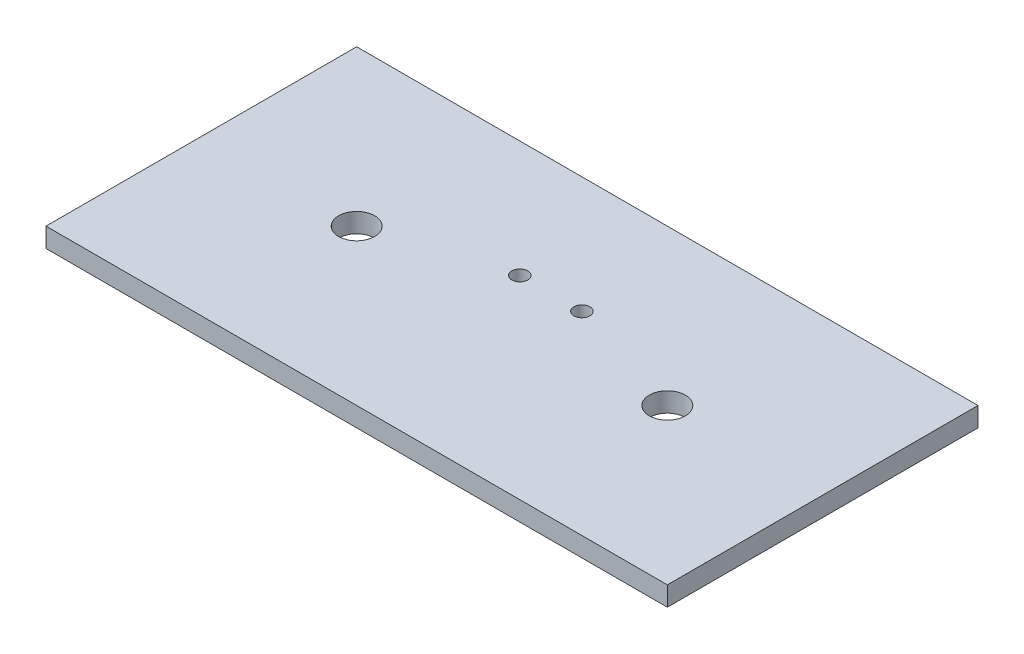
SolidWorks part; units mm, degrees
ref_plane "Front Plane" through (0, 0, 0) normal (0, 0, 1) x (1, 0, 0)
ref_plane "Top Plane" through (0, 0, 0) normal (0, 1, 0) x (1, 0, 0)
ref_plane "Right Plane" through (0, 0, 0) normal (1, 0, 0) x (0, 0, -1)
other "Configuration Table"
sketch "Sketch1" plane through (0, 0, 0) normal (0, 1, 0) x (1, 0, 0)
  line L1 (-25.4, -12.7) -> (25.4, -12.7)
  line L2 (-25.4, -12.7) -> (-25.4, 12.7)
  line L3 (-25.4, 12.7) -> (25.4, 12.7)
  line L4 (25.4, -12.7) -> (25.4, 12.7)
  line L5 (-25.4, -12.7) -> (25.4, 12.7) construction
  line L6 (-25.4, 12.7) -> (25.4, -12.7) construction
  point P0 (0, 0)
  dimension "D1" = 25.4
  dimension "D2" = 50.8
extrude "Boss-Extrude1" add sketch "Sketch1" along normal blind 1.5875
sketch "Sketch3" plane through (0, 1.5875, 0) normal (0, 1, 0) x (1, 0, 0)
  line L0 (-25.4, 6.35) -> (25.4, 6.35) construction
  line L1 (-25.4, 12.7) -> (-25.4, -12.7) construction
  line L2 (25.4, -12.7) -> (25.4, 12.7) construction
  line L3 (25.4, 12.7) -> (-25.4, 12.7) construction
  line L4 (-25.4, -6.35) -> (25.4, -6.35) construction
  line L5 (-25.4, -12.7) -> (25.4, -12.7) construction
  dimension "D1" = 6.35
  dimension "D2" = 6.35
sketch "Sketch2" plane through (0, 1.5875, 0) normal (0, 1, 0) x (1, 0, 0)
  line L0 (0, 0) -> (0, 3.175) construction
  line L1 (-2.54, 3.175) -> (2.54, 3.175) construction
  circle A0 centre (-2.54, 3.175) radius 0.65
  circle A1 centre (2.54, 3.175) radius 0.65
  point P5 (0, 3.175)
  dimension "D3" = 1.3
  dimension "D1" = 5.08
  dimension "D2" = 3.175
extrude "Cut-Extrude1" cut sketch "Sketch2" against normal through all
sketch "Sketch7" plane through (0, 1.5875, 0) normal (0, 1, 0) x (1, 0, 0)
  line L0 (-12.7, 0) -> (12.7, 0)
  point P4 (0, 0)
  dimension "D1" = 25.4
hole_wizard "#4 Clearance Hole2" positions "Sketch9" profile "Sketch10" hole size "#4" standard "ANSI Inch" end condition through all
sketch "Sketch9" plane through (0, 1.5875, 0) normal (0, 1, 0) x (1, 0, 0)
  point P0 (-12.7, 0)
  point P3 (12.7, 0)
sketch "Sketch10" plane through (-12.7, 1.5875, 0) normal (1, 0, 0) x (0, 0, 1)
  line L0 (0, 0) -> (0, 1.5875)
  line L1 (0, 1.5875) -> (1.4732, 1.5875)
  line L2 (1.4732, 1.5875) -> (1.4732, 0)
  line L5 (1.4732, 0) -> (0, 0)
  line L11 (0, -6.35) -> (0, 107.95) construction
  dimension "Thru Hole Dia." = 2.9464
  dimension "Thru Hole Depth" = 1.5875
